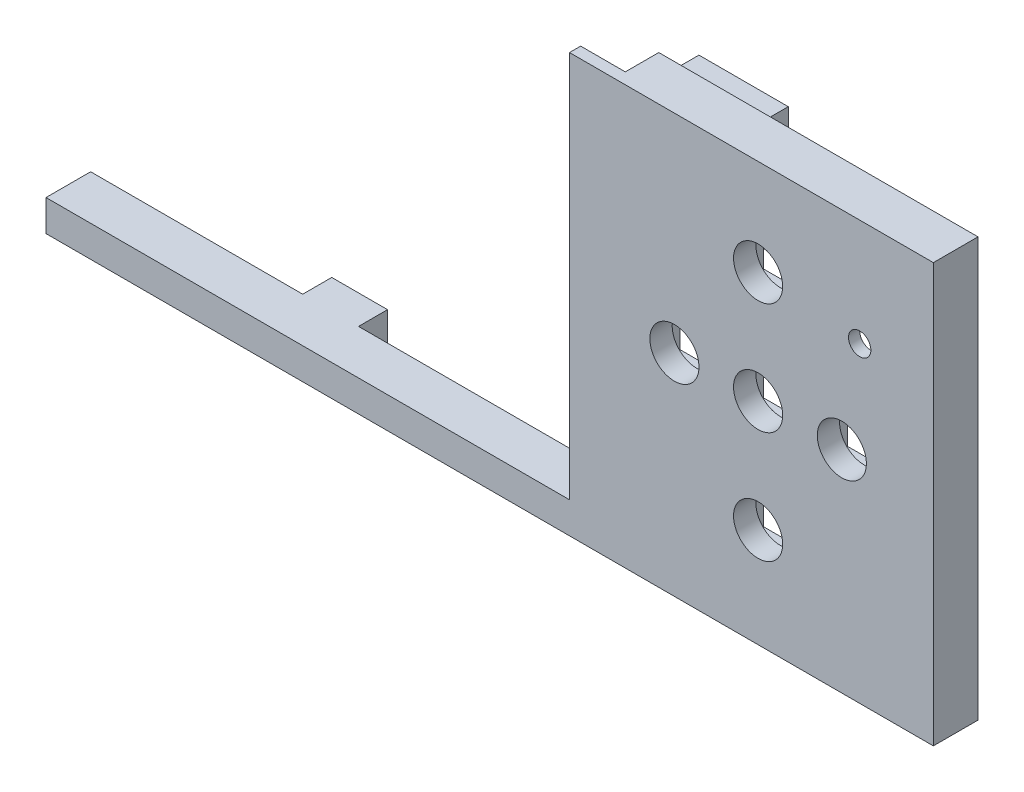
SolidWorks part; units mm, degrees
ref_plane "Płaszczyzna przednia" through (0, 0, 0) normal (0, 0, 1) x (1, 0, 0)
ref_plane "Płaszczyzna górna" through (0, 0, 0) normal (0, 1, 0) x (1, 0, 0)
ref_plane "Płaszczyzna prawa" through (0, 0, 0) normal (1, 0, 0) x (0, 0, -1)
sketch "Szkic1" plane through (0, 0, 0) normal (0, 0, 1) x (1, 0, 0)
  line L0 (-39.75, 0.15) -> (39.75, 0.15) construction
  line L1 (-39.75, -18.75) -> (39.75, -18.75)
  line L2 (-39.75, -18.75) -> (-39.75, 18.75)
  line L3 (-39.75, 18.75) -> (39.75, 18.75)
  line L4 (39.75, -18.75) -> (39.75, 18.75)
  line L5 (-39.75, -18.75) -> (39.75, 18.75) construction
  line L6 (-39.75, 18.75) -> (39.75, -18.75) construction
  line L7 (-39.75, 18.75) -> (7.15, 18.75)
  line L8 (-39.75, 18.75) -> (-39.75, -15.95)
  line L9 (-39.75, -15.95) -> (7.15, -15.95)
  line L10 (7.15, 18.75) -> (7.15, -15.95)
  line L11 (7.15, 1.4) -> (-39.75, 1.4) construction
  line L12 (24.05, -18.75) -> (24.05, 18.75) construction
  circle A0 centre (16.55, 0.15) radius 2.2
  circle A1 centre (24.05, 0.15) radius 2.2
  circle A2 centre (31.55, 0.15) radius 2.2
  circle A3 centre (24.05, -9.85) radius 2.2
  circle A4 centre (24.05, 10.15) radius 2.2
  circle A5 centre (33.15, 9.15) radius 1
  point P0 (0, 0)
  dimension "D6" = 7.5
  dimension "D9" = 4.4
  dimension "D11" = 26
  dimension "D13" = 2
  dimension "D1" = 37.5
  dimension "D2" = 79.5
  dimension "D3" = 34.7
  dimension "D4" = 46.9
  dimension "D5" = 1.25
  dimension "D7" = 7.5
  dimension "D8" = 10
  dimension "D10" = 16.9
  dimension "D12" = 9
extrude "Dodanie-wyciągnięcie1" add sketch "Szkic1" along normal blind 4 contours L3 L10 L9 L2 L1 L4 A5 A0 A1 A2 A3 A4
sketch "Szkic2" plane through (0, 0, 0) normal (0, 0, -1) x (-1, 0, 0)
  line L1 (-7.15, -15.95) -> (-11.15, -15.95)
  line L2 (-7.15, -15.95) -> (-7.15, 18.75)
  line L3 (-7.15, 18.75) -> (-11.15, 18.75)
  line L4 (-11.15, -15.95) -> (-11.15, 18.75)
  circle A0 centre (-33.15, 9.15) radius 5.75
  dimension "D1" = 11.5
  dimension "D2" = 4
extrude "Wytnij-wyciągnięcie1" cut sketch "Szkic2" against normal blind 3
sketch "Szkic3" plane through (0, 0, 0) normal (0, 0, -1) x (-1, 0, 0)
  line L0 (39.75, -18.75) -> (-39.75, -18.75) construction
  line L1 (15.75, -18.75) -> (20.75, -18.75)
  line L2 (15.75, -18.75) -> (15.75, -15.95)
  line L3 (15.75, -15.95) -> (20.75, -15.95)
  line L4 (20.75, -18.75) -> (20.75, -15.95)
  line L5 (39.75, -15.95) -> (-11.15, -15.95) construction
  line L6 (39.75, -18.75) -> (39.75, -15.95) construction
  line L7 (-11.15, 18.75) -> (-11.15, -15.95) construction
  line L8 (-20.15, 7.75) -> (-12.15, 7.75)
  line L9 (-20.15, 7.75) -> (-20.15, 17.75)
  line L10 (-20.15, 17.75) -> (-12.15, 17.75)
  line L11 (-12.15, 7.75) -> (-12.15, 17.75)
  line L12 (-11.15, 18.75) -> (-39.75, 18.75) construction
  line L14 (-34.05, -14.85) -> (-29.05, -14.85)
  line L15 (-34.05, -14.85) -> (-34.05, -7.85)
  line L16 (-34.05, -7.85) -> (-29.05, -7.85)
  line L17 (-29.05, -14.85) -> (-29.05, -7.85)
  circle A0 centre (-24.05, -9.85) radius 2.2 construction
  dimension "D7" = 5
  dimension "D9" = 5
  dimension "D1" = 24
  dimension "D2" = 5
  dimension "D3" = 8
  dimension "D4" = 1
  dimension "D5" = 1
  dimension "D6" = 10
  dimension "D8" = 5
  dimension "D10" = 7
extrude "Dodanie-wyciągnięcie2" add sketch "Szkic3" along normal blind 2.6
sketch "Szkic4" plane through (0, 0, 0) normal (0, 0, -1) x (-1, 0, 0)
  line L0 (-27.55, 13.65) -> (-29.5705, 13.65)
  line L1 (-27.55, -13.35) -> (-20.55, -13.35)
  line L2 (-27.55, -13.35) -> (-27.55, -6.35)
  line L3 (-27.55, -6.35) -> (-20.55, -6.35)
  line L4 (-20.55, -13.35) -> (-20.55, -6.35)
  line L5 (-27.55, -13.35) -> (-20.55, -6.35) construction
  line L6 (-27.55, -6.35) -> (-20.55, -13.35) construction
  line L7 (-27.55, -3.35) -> (-20.55, -3.35)
  line L8 (-27.55, -3.35) -> (-27.55, 3.65)
  line L9 (-27.55, 3.65) -> (-20.55, 3.65)
  line L10 (-20.55, -3.35) -> (-20.55, 3.65)
  line L11 (-27.55, -3.35) -> (-20.55, 3.65) construction
  line L12 (-27.55, 3.65) -> (-20.55, -3.35) construction
  line L13 (-20.05, -3.35) -> (-13.05, -3.35)
  line L14 (-20.05, -3.35) -> (-20.05, 3.65)
  line L15 (-20.05, 3.65) -> (-13.05, 3.65)
  line L16 (-13.05, -3.35) -> (-13.05, 3.65)
  line L17 (-20.05, -3.35) -> (-13.05, 3.65) construction
  line L18 (-20.05, 3.65) -> (-13.05, -3.35) construction
  line L19 (-35.05, -3.35) -> (-28.05, -3.35)
  line L20 (-35.05, -3.35) -> (-35.05, 3.65)
  line L21 (-35.05, 3.65) -> (-28.05, 3.65)
  line L22 (-28.05, -3.35) -> (-28.05, 3.65)
  line L23 (-35.05, -3.35) -> (-28.05, 3.65) construction
  line L24 (-35.05, 3.65) -> (-28.05, -3.35) construction
  line L25 (-27.55, 6.65) -> (-20.55, 6.65)
  line L26 (-27.55, 6.65) -> (-27.55, 13.65)
  line L27 (-27.55, 13.65) -> (-20.55, 13.65)
  line L28 (-20.55, 6.65) -> (-20.55, 13.65)
  line L29 (-27.55, 6.65) -> (-20.55, 13.65) construction
  line L30 (-27.55, 13.65) -> (-20.55, 6.65) construction
  line L31 (-27.55, 6.65) -> (-27.9719, 6.65)
  circle A0 centre (-33.15, 9.15) radius 5.75 construction
  arc A1 (-29.5705, 13.65) -> (-27.9719, 6.65) centre (-33.15, 9.15) cw
  point P0 (-24.05, -9.85)
  point P5 (-24.05, 0.15)
  point P11 (-16.55, 0.15)
  point P17 (-31.55, 0.15)
  point P23 (-24.05, 10.15)
  circle M19 centre (-24.05, 10.15) radius 2.2
  circle M20 centre (-24.05, -9.85) radius 2.2
  circle M21 centre (-31.55, 0.15) radius 2.2
  circle M22 centre (-24.05, 0.15) radius 2.2
  circle M23 centre (-16.55, 0.15) radius 2.2
  circle M24 centre (-33.15, 9.15) radius 5.75
  dimension "D2" = 5.75
  dimension "D1" = 7
extrude "Wytnij-wyciągnięcie3" cut sketch "Szkic4" against normal blind 2 contours L26 L0 M24 | L31 L26 M24 | L25 L28 L27 L26 M24 M19 | L7 L10 L9 L8 M22 | L19 L22 L21 L20 M24 M21 | L13 L16 L15 L14 M23 | L1 L4 L3 L2 M20
